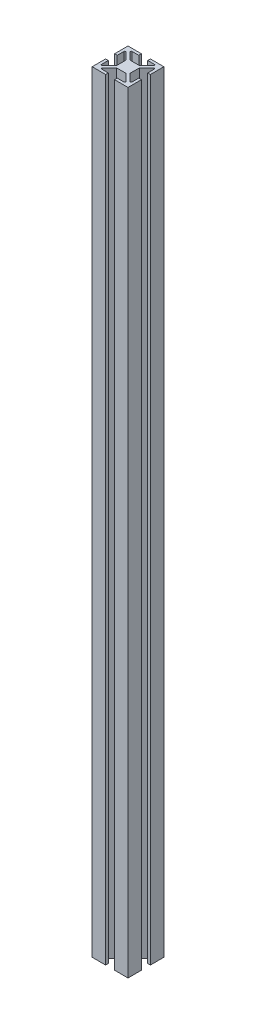
SolidWorks part; units mm, degrees
ref_plane "Plan de face" through (0, 0, 0) normal (0, 0, 1) x (1, 0, 0)
ref_plane "Plan de dessus" through (0, 0, 0) normal (0, 1, 0) x (1, 0, 0)
ref_plane "Plan de droite" through (0, 0, 0) normal (1, 0, 0) x (0, 0, -1)
sketch "Esquisse1" plane through (0, 0, 0) normal (0, 1, 0) x (1, 0, 0)
  line L0 (6.1245, 16.1036) -> (30.6226, 16.1036) construction
  line L6 (-11.5924, 0) -> (12.1076, 0) construction
  line L7 (0, 12.3466) -> (0, -12.7449) construction
  line L12 (-10, -10) -> (10, 10) construction
  line L59 (-10, -2.5) -> (-10, -10)
  line L60 (-10, -2.5) -> (-8.5, -2.5)
  line L69 (-8.5, -2.5) -> (-8.5, -6.2322)
  line L70 (-7.6464, -6.5858) -> (-3.75, -2.6893)
  line L73 (-6.5858, -7.6464) -> (-2.6893, -3.75)
  line L74 (-2.5, -8.5) -> (-6.2322, -8.5)
  line L75 (-2.5, -10) -> (-2.5, -8.5)
  line L76 (-2.5, -10) -> (-10, -10)
  line L77 (-2.5, 10) -> (-2.5, 8.5)
  line L78 (-2.5, 10) -> (-10, 10)
  line L79 (-10, 2.5) -> (-10, 10)
  line L80 (-10, 2.5) -> (-8.5, 2.5)
  line L81 (-8.5, 2.5) -> (-8.5, 6.2322)
  line L82 (-7.6464, 6.5858) -> (-3.75, 2.6893)
  line L83 (-6.5858, 7.6464) -> (-2.6893, 3.75)
  line L84 (-2.5, 8.5) -> (-6.2322, 8.5)
  line L85 (10, 2.5) -> (8.5, 2.5)
  line L86 (10, 2.5) -> (10, 10)
  line L87 (2.5, 10) -> (10, 10)
  line L88 (2.5, 10) -> (2.5, 8.5)
  line L89 (2.5, 8.5) -> (6.2322, 8.5)
  line L90 (6.5858, 7.6464) -> (2.6893, 3.75)
  line L91 (7.6464, 6.5858) -> (3.75, 2.6893)
  line L92 (8.5, 2.5) -> (8.5, 6.2322)
  line L93 (2.5, -10) -> (2.5, -8.5)
  line L94 (2.5, -10) -> (10, -10)
  line L95 (10, -2.5) -> (10, -10)
  line L96 (10, -2.5) -> (8.5, -2.5)
  line L97 (8.5, -2.5) -> (8.5, -6.2322)
  line L98 (7.6464, -6.5858) -> (3.75, -2.6893)
  line L99 (6.5858, -7.6464) -> (2.6893, -3.75)
  line L100 (2.5, -8.5) -> (6.2322, -8.5)
  line L101 (-3.75, 2.6893) -> (-3.75, -2.6893)
  line L102 (-2.6893, -3.75) -> (2.6893, -3.75)
  line L103 (-2.6893, 3.75) -> (2.6893, 3.75)
  line L104 (3.75, 2.6893) -> (3.75, -2.6893)
  arc A0 (-8.5, 6.2322) -> (-7.6464, 6.5858) centre (-8, 6.2322) cw
  arc A1 (-8.5, -6.2322) -> (-7.6464, -6.5858) centre (-8, -6.2322) ccw
  arc A2 (-6.5858, -7.6464) -> (-6.2322, -8.5) centre (-6.2322, -8) ccw
  arc A3 (6.5858, -7.6464) -> (6.2322, -8.5) centre (6.2322, -8) cw
  arc A4 (8.5, -6.2322) -> (7.6464, -6.5858) centre (8, -6.2322) cw
  arc A5 (7.6464, 6.5858) -> (8.5, 6.2322) centre (8, 6.2322) cw
  arc A6 (6.2322, 8.5) -> (6.5858, 7.6464) centre (6.2322, 8) cw
  arc A7 (-6.5858, 7.6464) -> (-6.2322, 8.5) centre (-6.2322, 8) cw
  point P7 (-2.5, -9.25)
  point P8 (2.5, -9.25)
  point P15 (-8.5, -7.4393)
  point P51 (0, 0)
  point P52 (-7.4393, -8.5)
  dimension "D2" = 5
  dimension "D7" = 0.5
  dimension "D1" = 20
  dimension "D3" = 4
  dimension "D4" = 7.5
  dimension "D5" = 1.5
  dimension "D6" = 1.5
extrude "Boss.-Extru.1" add sketch "Esquisse1" along normal blind 430
